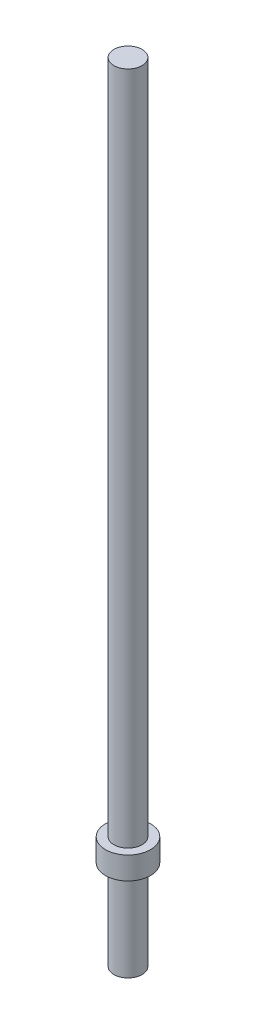
SolidWorks part; units mm, degrees
ref_plane "Front Plane" through (0, 0, 0) normal (0, 0, 1) x (1, 0, 0)
ref_plane "Top Plane" through (0, 0, 0) normal (0, 1, 0) x (1, 0, 0)
ref_plane "Right Plane" through (0, 0, 0) normal (1, 0, 0) x (0, 0, -1)
sketch "Sketch1" plane through (0, 0, 0) normal (0, 1, 0) x (1, 0, 0)
  circle A0 centre (0, 0) radius 2.5
extrude "Boss-Extrude1" add sketch "Sketch1" along normal blind 120
sketch "Sketch2" plane through (0, 0, 0) normal (0, 1, 0) x (1, 0, 0)
  circle A0 centre (0, 0) radius 4
extrude "Boss-Extrude2" add sketch "Sketch2" against normal blind 4
sketch "Sketch3" plane through (0, 0, 0) normal (0, 1, 0) x (1, 0, 0)
  circle A0 centre (0, 0) radius 2.5
extrude "Boss-Extrude3" add sketch "Sketch3" against normal blind 20
